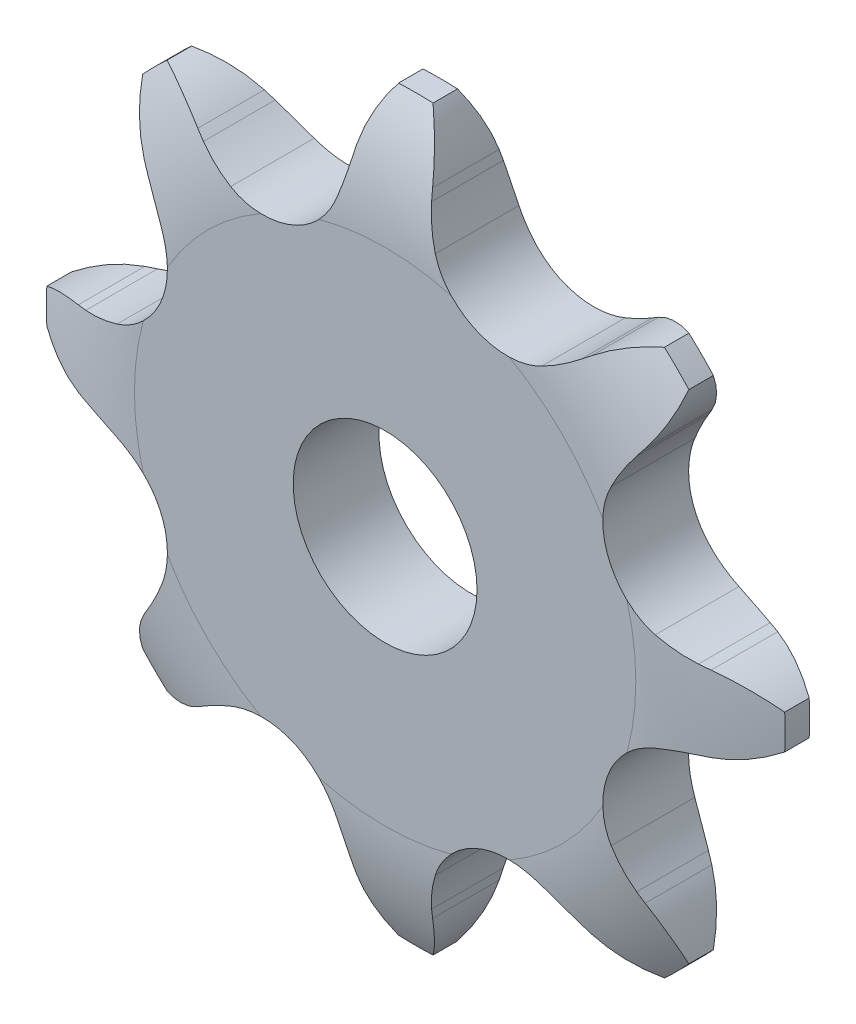
SolidWorks part; units mm, degrees
ref_plane "Front Plane" through (0, 0, 0) normal (0, 0, 1) x (1, 0, 0)
ref_plane "Top Plane" through (0, 0, 0) normal (0, 1, 0) x (1, 0, 0)
ref_plane "Right Plane" through (0, 0, 0) normal (1, 0, 0) x (0, 0, -1)
sketch "Sketch0" plane through (0, 0, 0) normal (0, 0, 1) x (1, 0, 0)
  line L0 (4, -9.6569) -> (0, 0) construction
  line L1 (0, 0) -> (9.6569, -4) construction
  line L2 (0, 0) -> (-4, -9.6569) construction
  line L3 (4, -9.6569) -> (9.6569, -4) construction
  line L4 (4, -9.6569) -> (-4, -9.6569) construction
  line L5 (6.4283, -8.1776) -> (6.1599, -7.9825)
  line L6 (4, -9.6569) -> (0, -11.3137) construction
  line L7 (1.2369, -10.3279) -> (1.2888, -10.0002)
  line L8 (0, -9.6569) -> (0, -12.0569) construction
  line L9 (5.0779, -7.3452) -> (2.3095, -13.2821) construction
  line L10 (0, 0) -> (0, -9.6569) construction
  line L11 (6.1599, -7.9825) -> (2.3095, -13.2821) construction
  line L12 (0, -12.0569) -> (0, -12.7231) construction
  line L13 (8.9497, -4.7071) -> (6.4283, -8.1776) construction
  circle A0 centre (0, 0) radius 12.0569 construction
  circle A1 centre (0, 0) radius 10.4525 construction
  arc A2 (-4.2727, -13.7535) -> (12.7464, -6.7039) centre (0, 0) ccw
  circle A3 centre (0, 0) radius 12.7231 construction
  circle A4 centre (4, -9.6569) radius 2.5 construction
  arc A7 (5.0779, -7.3452) -> (1.6032, -8.7845) centre (4, -9.6569) ccw
  circle A8 centre (4, -9.6569) radius 2.5506 construction
  arc A9 (6.4283, -8.1776) -> (12.7464, -6.7039) centre (8.9497, -4.7071) ccw
  arc A10 (6.1599, -7.9825) -> (5.0779, -7.3452) centre (2.3095, -13.2821) ccw
  arc A11 (1.2369, -10.3279) -> (-4.2727, -13.7535) centre (-3, -9.6569) cw
  arc A12 (1.2888, -10.0002) -> (1.6032, -8.7845) centre (7.7588, -11.0249) cw
  dimension "D1" = 2.5506
  dimension "R" = 2.5506
sketch "Sketch1" plane through (0, 0, 0) normal (1, 0, 0) x (0, 0, -1)
  line L0 (1.4, 0) -> (-1.4, 0)
  line L1 (-1.4, 0) -> (-1.4, 8.1839)
  line L2 (-1.4, 10.4525) -> (0, 10.4525) construction
  line L3 (-0.4, 12.0569) -> (0.4, 12.0569)
  line L5 (1.4, 8.1839) -> (1.4, 0)
  line L7 (0, 12.0569) -> (0, 0) construction
  line L8 (-1.4, 8.1839) -> (1.4, 8.1839) construction
  line L9 (0, 12.0569) -> (0, -12.0569) construction
  line L10 (-1.4, 8.1839) -> (-1.4, 12.0569) construction
  line L11 (-1.4, 12.0569) -> (-0.4, 12.0569) construction
  line L12 (0.4, 12.0569) -> (1.4, 12.0569) construction
  line L13 (1.4, 12.0569) -> (1.4, 8.1839) construction
  line L14 (0, 0) -> (-6.4008, 0) construction
  line L15 (-1.4, 10.4525) -> (-1.4, 5.1525) construction
  line L22 (1.4, 0) -> (-10.6, 0) construction
  line L24 (-1.4, 0) -> (-1.4, 5.1525) construction
  arc A0 (-0.4, 12.0569) -> (-1.4, 8.1839) centre (6.6, 8.1839) ccw
  arc A1 (0.4, 12.0569) -> (1.4, 8.1839) centre (-6.6, 8.1839) cw
  dimension "R" = 8
revolve "Revolve1" add sketch "Sketch1" angle 360 mid plane about L0
extrude "Cut-Extrude1" cut sketch "Sketch0" against normal through all and the other way through all
pattern_circular "CirPattern1" count 8 over 360 about axis through (0, 0, 0) along (0, 0, 1) of "Cut-Extrude1"
sketch "Sketch2" plane through (0, 0, 0) normal (0, 0, 1) x (1, 0, 0)
  circle A0 centre (0, 0) radius 3 construction
  circle A1 centre (0, 0) radius 6.5
  circle A2 centre (0, 0) radius 12.055 construction
  dimension "Bore" = 6
  dimension "Hub Dia." = 13
  dimension "OD" = 24.11
extrude "Boss-Extrude1" add sketch "Sketch2" along normal up to vertex (10.6 mm away) from surface at 1.4 starting at face at (0, 0, 1.4)
sketch "Sketch3" plane through (0, 0, 0) normal (0, 0, 1) x (1, 0, 0)
  circle A0 centre (0, 0) radius 3 construction
  circle A1 centre (0, 0) radius 3
extrude "Cut-Extrude2" cut sketch "Sketch3" along normal through all and the other way through all
sketch "Sketch4" plane through (0, 0, 0) normal (1, 0, 0) x (0, 0, -1)
  line L0 (-10.6, 6.5) -> (-10.6, 6)
  line L1 (-1.4, 12.0569) -> (-3.5, 12.0569)
  line L2 (-1.4, 12.0569) -> (-1.4, 5.1525)
  line L3 (-1.4, 5.1525) -> (-3.5, 5.1525)
  line L4 (-3.5, 12.0569) -> (-3.5, 5.1525)
  line L9 (-10.6, 6) -> (-10.1, 6.5)
  line L10 (-10.1, 6.5) -> (-10.6, 6.5)
  dimension "C" = 0.5
  dimension "D3" = 2.1
revolve "Cut-Revolve1" cut sketch "Sketch4" angle 360 mid plane about L22
sketch "Sketch5" plane through (0, 0, 0) normal (0, 0, 1) x (1, 0, 0)
  circle A0 centre (0, 0) radius 12.055 construction
  circle A1 centre (0, 0) radius 12.055
extrude "Cut-Extrude3" [suppressed] cut sketch "Sketch5" against normal through all and the other way through all flip side to cut
sketch "Sketch6" plane through (0, 0, 1.4) normal (0, 0, 1) x (1, 0, 0)
  circle A0 centre (0, 0) radius 9
  dimension "D1" = 18
extrude "Cut-Extrude4" cut sketch "Sketch6" along normal blind 10
sketch "Sketch7" plane through (0, 0, 1.4) normal (0, 0, 1) x (1, 0, 0)
  line L0 (-3.0239, 7.3004) -> (3.0239, 7.3004) construction
  arc A0 (-4.058, 7.1069) -> (-2.1559, 7.8948) centre (-4, 9.6569) ccw construction
  arc A1 (2.1559, 7.8948) -> (4.058, 7.1069) centre (4, 9.6569) ccw construction
  circle A2 centre (0, 0) radius 7.3004 construction
  dimension "D1" = 14.6008
equation "\"360/N@Sketch0\" = 360/\"Teeth@CirPattern1\""
equation "\"Ds@Sketch0\" = 1.005 * \"Dr@Sketch0\" + ( 0.003 * 25.4 ) "
equation "\"R@Sketch0\" = 1/2 * \"Ds@Sketch0\""
equation "\"A@Sketch0\" = 35 +  ( 60 / \"Teeth@CirPattern1\" ) "
equation "\"B@Sketch0\" = 18 -  ( 56 / \"Teeth@CirPattern1\" )"
equation "\"ac@Sketch0\" = 0.8 * \"Dr@Sketch0\""
equation "\"ab@Sketch0\" = 1.4 * \"Dr@Sketch0\""
equation "\"J@Sketch0\" = 0.3 * \"Pitch@Sketch0\""
equation "\"D3@Sketch4\" = \"t@Sketch1\" * 3 / 4"
